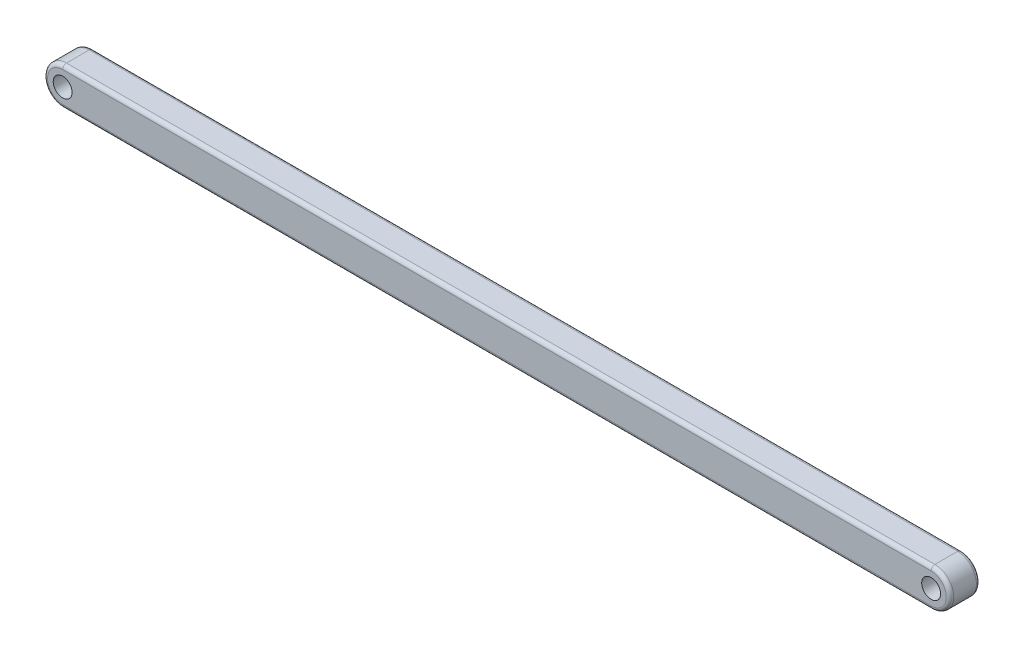
SolidWorks part; units mm, degrees
ref_plane "Front Plane" through (0, 0, 0) normal (0, 0, 1) x (1, 0, 0)
ref_plane "Top Plane" through (0, 0, 0) normal (0, 1, 0) x (1, 0, 0)
ref_plane "Right Plane" through (0, 0, 0) normal (1, 0, 0) x (0, 0, -1)
sketch "Sketch1" plane through (0, 0, 0) normal (0, 0, 1) x (1, 0, 0)
  line L0 (-46.2069, 0) -> (68.7931, 0) construction
  line L1 (-46.2069, 2.5) -> (68.7931, 2.5)
  line L2 (-46.2069, -2.5) -> (68.7931, -2.5)
  arc A0 (-46.2069, 2.5) -> (-46.2069, -2.5) centre (-46.2069, 0) ccw
  arc A1 (68.7931, -2.5) -> (68.7931, 2.5) centre (68.7931, 0) ccw
  circle A2 centre (-46.2069, 0) radius 1.25
  circle A3 centre (68.7931, 0) radius 1.25
  point P3 (11.2931, 0)
  dimension "D3" = 2.5
  dimension "D4" = 2.5
  dimension "D1" = 115
  dimension "D2" = 5
extrude "Boss-Extrude1" add sketch "Sketch1" along normal blind 4
fillet "Fillet1" radius 0.5 8 edges at (71.2931, 0, 0) (11.2931, -2.5, 0) (-48.7069, 0, 0) (71.2931, 0, 4) (11.2931, -2.5, 4) (-48.7069, 0, 4) (11.2931, 2.5, 0) (11.2931, 2.5, 4)
scale "缩放比例1" scale about centroid uniform scaling yes scale factor 2
